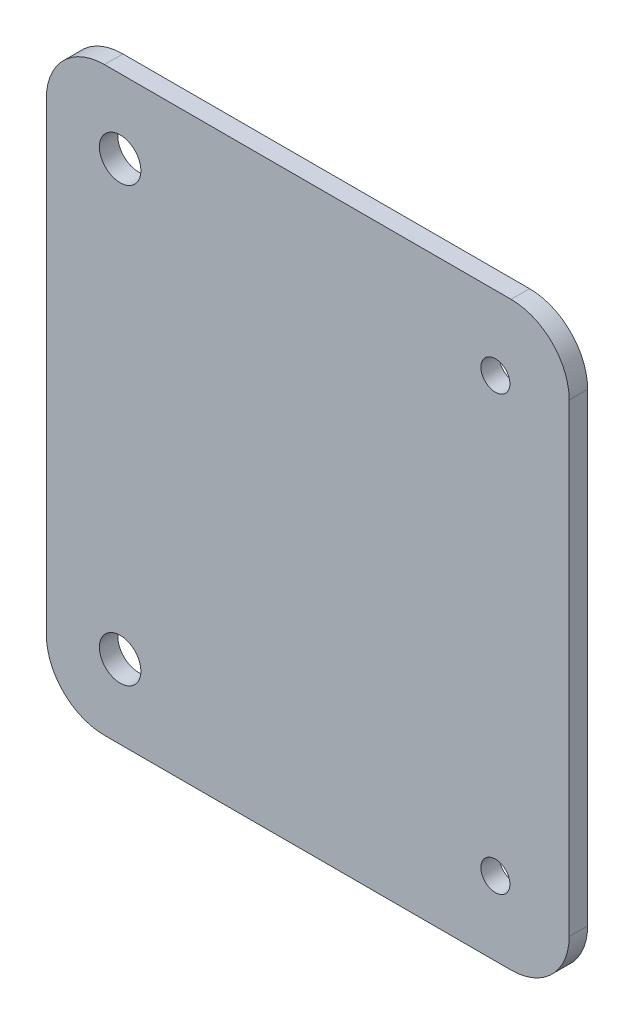
SolidWorks part; units mm, degrees
ref_plane "Front Plane" through (0, 0, 0) normal (0, 0, 1) x (1, 0, 0)
ref_plane "Top Plane" through (0, 0, 0) normal (0, 1, 0) x (1, 0, 0)
ref_plane "Right Plane" through (0, 0, 0) normal (1, 0, 0) x (0, 0, -1)
sketch "Sketch1" plane through (0, 0, 0) normal (0, 0, 1) x (1, 0, 0)
  line L0 (35, 45) -> (-35, 45) construction
  line L1 (-45, -55) -> (45, -55)
  line L2 (-45, -55) -> (-45, 45)
  line L3 (-45, 45) -> (45, 45)
  line L4 (45, -55) -> (45, 45)
  line L5 (-43.1231, -55) -> (43.1231, -55) construction
  line L6 (-45, 35) -> (-45, 25) construction
  line L7 (45, 25) -> (45, 35) construction
  circle A1 centre (32.3, -42.3) radius 2.5 construction
  circle A2 centre (-32.3, -42.3) radius 3.57 construction
  circle A5 centre (32.3, -42.3) radius 2.5
  circle A6 centre (-32.3, -42.3) radius 3.57
  circle A8 centre (-32.3, 32.3) radius 3.57 construction
  circle A9 centre (-32.3, 32.3) radius 3.57
  circle A10 centre (32.3, 32.3) radius 2.5 construction
  circle A11 centre (32.3, 32.3) radius 2.5
extrude "Boss-Extrude1" add sketch "Sketch1" against normal blind 3.18 from vertex
fillet "Fillet1" radius 10 4 edges at (45, -55, 17.1398) (45, 45, 17.1398) (-45, 45, 17.1398) (-45, -55, 17.1398)
